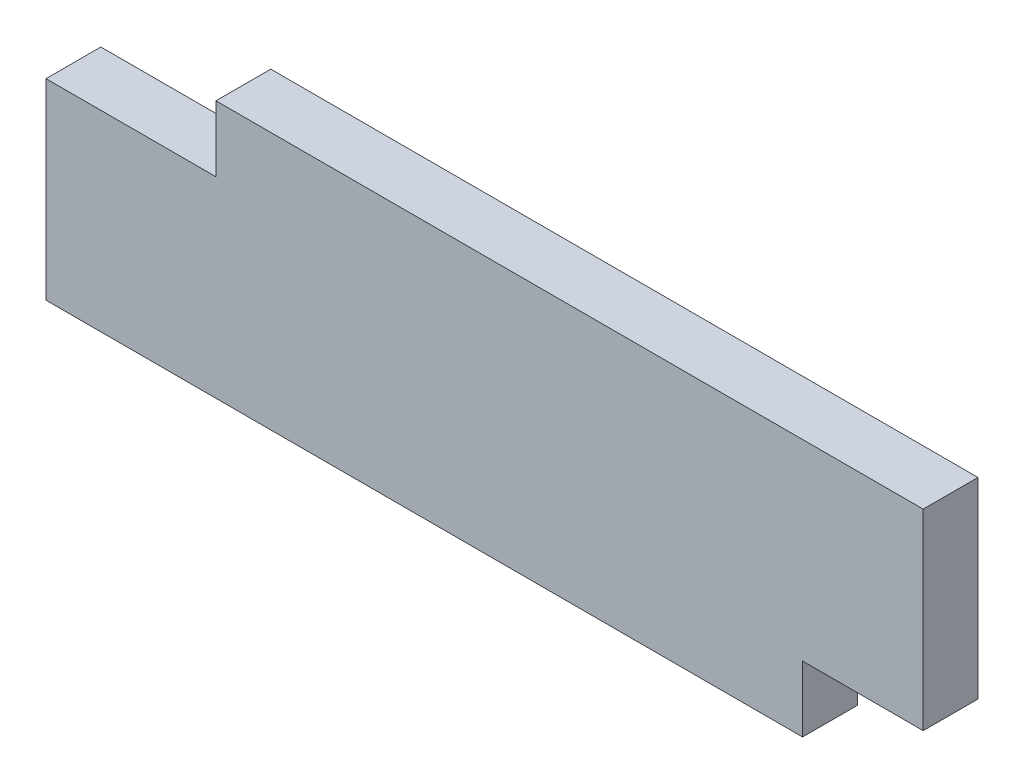
SolidWorks part; units mm, degrees
ref_plane "Front Plane" through (0, 0, 0) normal (0, 0, 1) x (1, 0, 0)
ref_plane "Top Plane" through (0, 0, 0) normal (0, 1, 0) x (1, 0, 0)
ref_plane "Right Plane" through (0, 0, 0) normal (1, 0, 0) x (0, 0, -1)
sketch "Sketch1" plane through (0, 0, 0) normal (0, 0, 1) x (1, 0, 0)
  line L1 (-130, -23.5) -> (30, -23.5)
  line L2 (-130, -23.5) -> (-130, 23.5)
  line L3 (-130, 23.5) -> (30, 23.5)
  line L4 (30, -23.5) -> (30, 23.5)
extrude "Boss-Extrude1" add sketch "Sketch1" along normal blind 10
sketch "Sketch3" plane through (0, 0, 0) normal (0, 0, -1) x (-1, 0, 0)
  line L0 (-30, -11.5) -> (130, -11.5) construction
  line L1 (-30, -11.5) -> (-8, -11.5)
  line L2 (-8, -23.5) -> (-8, -26.65) construction
  line L3 (-8, -11.5) -> (-8, -23.5)
  line L4 (-30, 11.5) -> (130, 11.5) construction
  line L5 (99, 11.5) -> (130, 11.5)
  line L6 (139, 23.5) -> (139, 26.65) construction
  line L7 (139, 23.5) -> (139, 26.65)
  line L8 (99, 11.5) -> (99, 23.5)
  line L9 (99, 23.5) -> (99, 26.65) construction
  line L10 (-30, -23.5) -> (-30, 23.5) construction
  line L11 (130, -23.5) -> (-30, -23.5) construction
  line L12 (-30, -23.5) -> (-30, -11.5)
  line L13 (-8, -23.5) -> (-30, -23.5)
  line L14 (-30, 23.5) -> (130, 23.5) construction
  line L15 (130, 23.5) -> (130, -23.5) construction
  line L16 (99, 23.5) -> (130, 23.5)
  line L17 (130, 23.5) -> (130, 11.5)
  point P4 (-8, -11.5)
  point P12 (99, 11.5)
  line M8 (130, -23.5) -> (130, 23.5)
  line M9 (130, 23.5) -> (-30, 23.5)
  line M10 (-30, 23.5) -> (-30, -23.5)
  line M11 (-30, -23.5) -> (130, -23.5)
  dimension "D1" = 40
extrude "Cut-Extrude1" cut sketch "Sketch3" against normal blind 10 contours L8 L5 M8 M9 | L3 L1 M10 M11
